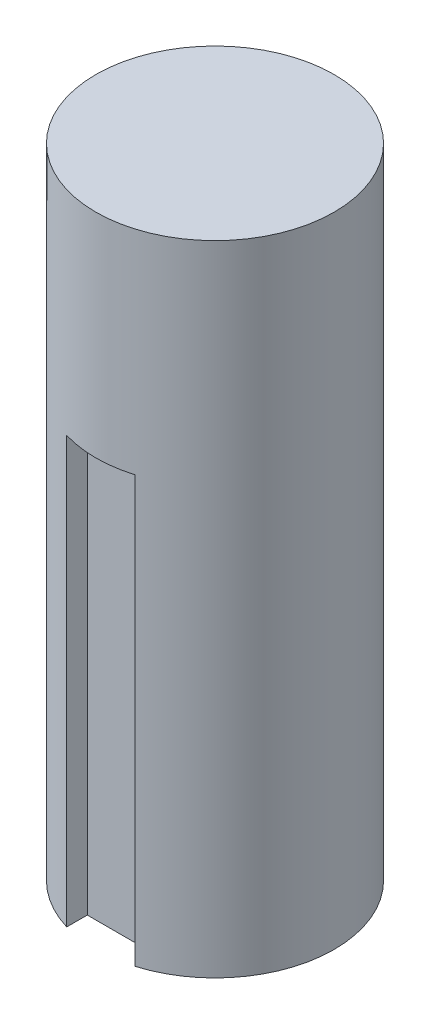
SolidWorks part; units mm, degrees
ref_plane "Front Plane" through (0, 0, 0) normal (0, 0, 1) x (1, 0, 0)
ref_plane "Top Plane" through (0, 0, 0) normal (0, 1, 0) x (1, 0, 0)
ref_plane "Right Plane" through (0, 0, 0) normal (1, 0, 0) x (0, 0, -1)
sketch "Sketch1" plane through (0, 0, 0) normal (0, 1, 0) x (1, 0, 0)
  circle A0 centre (0, 0) radius 28
  dimension "D1" = 56
extrude "Boss-Extrude1" add sketch "Sketch1" along normal blind 150
sketch "Sketch2" plane through (0, 0, 0) normal (0, -1, 0) x (1, 0, 0)
  line L1 (-8, 22) -> (8, 22)
  line L2 (-8, 22) -> (-8, 28)
  line L3 (-8, 28) -> (8, 28)
  line L4 (8, 22) -> (8, 28)
  line L5 (-8, 22) -> (8, 28) construction
  line L6 (-8, 28) -> (8, 22) construction
  point P0 (0, 25)
  dimension "D1" = 16
  dimension "D2" = 6
  dimension "D3" = 25
extrude "Cut-Extrude1" cut sketch "Sketch2" against normal blind 100
